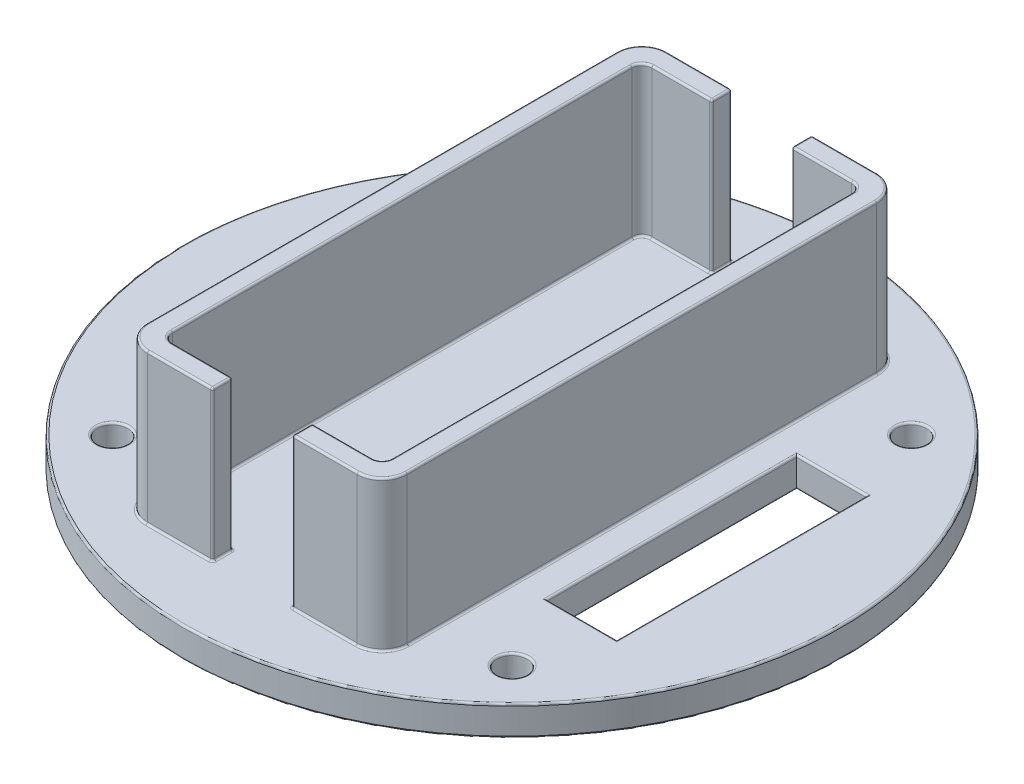
SolidWorks part; units mm, degrees
ref_plane "Front Plane" through (0, 0, 0) normal (0, 0, 1) x (1, 0, 0)
ref_plane "Top Plane" through (0, 0, 0) normal (0, 1, 0) x (1, 0, 0)
ref_plane "Right Plane" through (0, 0, 0) normal (1, 0, 0) x (0, 0, -1)
sketch "Sketch1" plane through (0, 0, 0) normal (0, 1, 0) x (1, 0, 0)
  circle A0 centre (0, 0) radius 33
  dimension "D1" = 66
extrude "Boss-Extrude1" add sketch "Sketch1" along normal blind 3
sketch "Sketch2" plane through (0, 3, 0) normal (0, 1, 0) x (1, 0, 0)
  line L0 (-4, 25) -> (-12, 25)
  line L1 (-12, 25) -> (-12, -25)
  line L2 (-12, -25) -> (-4, -25)
  line L3 (0, 0) -> (0, -33) construction
  line L4 (12, -25) -> (4, -25)
  line L5 (12, 25) -> (12, -25)
  line L6 (4, 25) -> (12, 25)
  line L7 (0, 0) -> (33, 0) construction
  circle A0 centre (0, 0) radius 33 construction
  dimension "D1" = 12
  dimension "D2" = 25
  dimension "D3" = 8
extrude "Extrude-Thin1" add sketch "Sketch2" along normal blind 15 thin thin type mid plane wall 2
sketch "Sketch3" plane through (0, 3, 0) normal (0, 1, 0) x (1, 0, 0)
  line L0 (0, -9.9) -> (0, 9.9) construction
  line L1 (-23, 12.5) -> (-16, 12.5)
  line L2 (-23, 12.5) -> (-23, -12.5)
  line L3 (-23, -12.5) -> (-16, -12.5)
  line L4 (-16, 12.5) -> (-16, -12.5)
  line L5 (16, 12.5) -> (16, -12.5)
  line L6 (23, -12.5) -> (16, -12.5)
  line L7 (23, 12.5) -> (23, -12.5)
  line L8 (23, 12.5) -> (16, 12.5)
  point P11 (-16, 0)
  dimension "D1" = 7
  dimension "D2" = 25
  dimension "D3" = 16
extrude "Cut-Extrude1" cut sketch "Sketch3" against normal up to next
sketch "Sketch4" plane through (0, 3, 0) normal (0, 1, 0) x (1, 0, 0)
  line L0 (0, -9.9) -> (0, 9.9) construction
  line L1 (-9.9, 0) -> (9.9, 0) construction
  circle A5 centre (-20, -20) radius 1.5
  circle A6 centre (20, -20) radius 1.5
  circle A7 centre (20, 20) radius 1.5
  circle A8 centre (-20, 20) radius 1.5
  dimension "D1" = 3
  dimension "D2" = 20
  dimension "D3" = 20
extrude "Cut-Extrude2" cut sketch "Sketch4" against normal up to next
fillet "Fillet2" radius 1 4 edges at (11, 10.5, -24) (-11, 10.5, -24) (-11, 10.5, 24) (11, 10.5, 24)
fillet "Fillet3" radius 2.5 4 edges at (13, 10.5, -26) (-13, 10.5, -26) (-13, 10.5, 26) (13, 10.5, 26)
fillet "Fillet5" radius 0.2 82 edges at (7.25, 18, 26) (12.2678, 18, 25.2678) (13, 18, 0) (12.2678, 18, -25.2678) (-7.25, 18, 26) (-12.2678, 18, 25.2678) (-13, 18, 0) (-12.2678, 18, -25.2678) (-7, 18, -24) (-10.7071, 18, -23.7071) (-11, 18, 0) (-10.7071, 18, 23.7071) (7, 18, -24) (10.7071, 18, -23.7071) (11, 18, 0) (10.7071, 18, 23.7071) (4, 10.5, -26) (7.25, 18, -26) (-4, 10.5, -26) (-7.25, 18, -26) (-4, 10.5, 24) (-7, 18, 24) (4, 10.5, 24) (7, 18, 24) (0, 0, 33) (19.5, 0, 12.5) (16, 0, 0) (19.5, 0, -12.5) (23, 0, 0) (-16, 0, 0) (-19.5, 0, 12.5) (-23, 0, 0) (-19.5, 0, -12.5) (-20, 0, 21.5) (20, 0, 21.5) (20, 0, -18.5) (-20, 0, -18.5) (-10.7071, 3, -23.7071) (-7, 3, -24) (-4, 3, -25) (-7.25, 3, -26) (-12.2678, 3, -25.2678) (-13, 3, 0) (-12.2678, 3, 25.2678) (-7.25, 3, 26) (-4, 3, 25) (-7, 3, 24) (-10.7071, 3, 23.7071) (-11, 3, 0) (4, 3, 25) (7.25, 3, 26) (12.2678, 3, 25.2678) (13, 3, 0) (12.2678, 3, -25.2678) (7.25, 3, -26) (4, 3, -25) (7, 3, -24) (10.7071, 3, -23.7071) (11, 3, 0) (10.7071, 3, 23.7071) (7, 3, 24) (0, 3, 33) (16, 3, 0) (19.5, 3, 12.5) (23, 3, 0) (19.5, 3, -12.5) (-19.5, 3, 12.5) (-16, 3, 0) (-19.5, 3, -12.5) (-23, 3, 0) (-20, 3, 21.5) (20, 3, 18.5) (20, 3, -18.5) (-20, 3, -21.5) (-4, 10.5, 26) (4, 10.5, 26) (-4, 10.5, -24) (4, 10.5, -24) (4, 18, 25) (4, 18, -25) (-4, 18, -25) (-4, 18, 25)
equation "\"D3@Sketch4\"=\"D2@Sketch4\""
